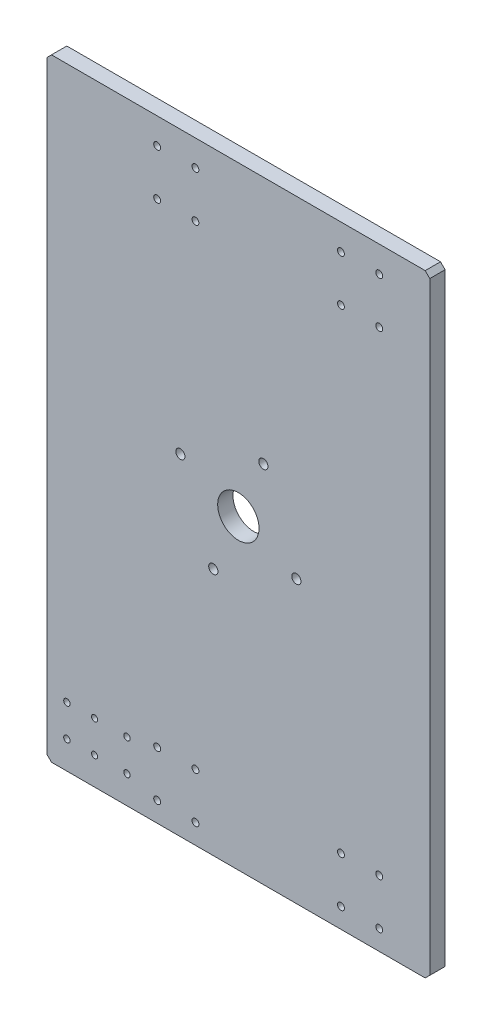
SolidWorks part; units mm, degrees
ref_plane "Plan de face" through (0, 0, 0) normal (0, 0, 1) x (1, 0, 0)
ref_plane "Plan de dessus" through (0, 0, 0) normal (0, 1, 0) x (1, 0, 0)
ref_plane "Plan de droite" through (0, 0, 0) normal (1, 0, 0) x (0, 0, -1)
sketch "Esquisse1" plane through (0, 0, 0) normal (0, 0, 1) x (1, 0, 0)
  line L1 (-125, -200) -> (125, -200)
  line L2 (-125, -200) -> (-125, 200)
  line L3 (-125, 200) -> (125, 200)
  line L4 (125, -200) -> (125, 200)
  line L5 (-125, -200) -> (125, 200) construction
  line L6 (-125, 200) -> (125, -200) construction
  point P0 (0, 0)
  dimension "D1" = 400
  dimension "D2" = 250
extrude "Boss.-Extru.1" add sketch "Esquisse1" along normal blind 10
ref_plane "Plan1" through (0, 0, 0) normal (1, 0, 0) x (0, 0, -1)
ref_plane "Plan2" through (0, 0, 0) normal (0, 1, 0) x (1, 0, 0)
sketch "Esquisse2" plane through (0, 0, 0) normal (0, 0, -1) x (-1, 0, 0)
  circle A0 centre (0, 0) radius 13.5
  dimension "D1" = 27
extrude "Enlèv. mat.-Extru.1" cut sketch "Esquisse2" against normal through all
chamfer "Chanfrein1" distance 3 angle 45 4 edges at (-125, -200, 5) (125, -200, 5) (125, 200, 5) (-125, 200, 5)
hole_wizard "Trou taraudé M51" positions "Esquisse6" profile "Esquisse5" tap size "M5" standard "ISO" end condition through all
sketch "Esquisse6" plane through (0, 0, 10) normal (0, 0, 1) x (1, 0, 0)
  point P0 (-72.6985, -161.0797)
  point P3 (-72.6985, -181.8387)
  point P6 (-111.9372, -181.8387)
  point P9 (-111.9372, -161.0797)
sketch "Esquisse5" plane through (-72.6985, -161.0797, 10) normal (1, 0, 0) x (0, -1, 0)
  line L0 (0, 0) -> (0, 10)
  line L1 (0, 10) -> (2.1, 10)
  line L2 (2.1, 10) -> (2.1, 0)
  line L5 (2.1, 0) -> (0, 0)
  line L11 (0, -6.35) -> (0, 107.95) construction
  dimension "Diamètre du trou pour taraudage jusqu'au prochain" = 4.2
  dimension "Profondeur du trou pour taraudage jusqu'au prochain" = 10
cosmetic thread "Filetage de perçage3" parameters "D2"=5
cosmetic thread "Filetage de perçage4" parameters "D2"=5
cosmetic thread "Filetage de perçage5" parameters "D2"=5
cosmetic thread "Filetage de perçage6" parameters "D2"=5
hole_wizard "Trous de centrage Ø4.0mm2" positions "Esquisse9" profile "Esquisse8" hole size "Ø4.0" standard "ISO" end condition through all
sketch "Esquisse9" plane through (0, 0, 10) normal (0, 0, 1) x (1, 0, 0)
  point P0 (-93.8631, -161.0797)
  point P3 (-93.8631, -181.8387)
sketch "Esquisse8" plane through (-93.8631, -161.0797, 10) normal (1, 0, 0) x (0, -1, 0)
  line L0 (0, 0) -> (0, 10)
  line L1 (0, 10) -> (2, 10)
  line L2 (2, 10) -> (2, 0)
  line L5 (2, 0) -> (0, 0)
  line L11 (0, -6.35) -> (0, 107.95) construction
  dimension "Diamètre du perçage jusqu'au prochain" = 4
  dimension "Profondeur du perçage jusqu'au prochain" = 10
sketch "Esquisse10" plane through (0, 0, 10) normal (0, 0, 1) x (1, 0, 0)
  circle A0 centre (0, 0) radius 41.25 construction
  dimension "D1" = 82.5
hole_wizard "Trous de centrage Ø6.0mm2" positions "Esquisse26" profile "Esquisse25" hole size "Ø6.0" standard "ISO" end condition through all
sketch "Esquisse26" plane through (0, 0, 10) normal (0, 0, 1) x (1, 0, 0)
  point P0 (16.3571, 37.8683)
  point P2 (37.8683, -16.3571)
  point P4 (-16.3571, -37.8683)
  point P6 (-37.8683, 16.3571)
sketch "Esquisse25" plane through (16.3571, 37.8683, 10) normal (1, 0, 0) x (0, -1, 0)
  line L0 (0, 0) -> (0, 10)
  line L1 (0, 10) -> (3, 10)
  line L2 (3, 10) -> (3, 0)
  line L5 (3, 0) -> (0, 0)
  line L11 (0, -6.35) -> (0, 107.95) construction
  dimension "Diamètre du perçage jusqu'au prochain" = 6
  dimension "Profondeur du perçage jusqu'au prochain" = 10
hole_wizard "Dégagement M41" positions "Esquisse28" profile "Esquisse27" hole size "M4" standard "JIS" end condition through all
sketch "Esquisse28" plane through (0, 0, 0) normal (0, 0, -1) x (-1, 0, 0)
  point P0 (28, -187)
  point P2 (28, -157)
  point P4 (53, -157)
  point P6 (53, -187)
sketch "Esquisse27" plane through (-28, -187, 0) normal (1, 0, 0) x (0, 1, 0)
  line L0 (0, 0) -> (0, 10)
  line L1 (0, 10) -> (2.25, 10)
  line L2 (2.25, 10) -> (2.25, 0)
  line L5 (2.25, 0) -> (0, 0)
  line L11 (0, -6.35) -> (0, 107.95) construction
  dimension "Diamètre du perçage jusqu'au prochain" = 4.5
  dimension "Profondeur du perçage jusqu'au prochain" = 10
pattern_linear "Répétition linéaire1" count 2 spacing 120 along (1, 0, 0) count 2 spacing 340 along (0, 1, 0) of "Dégagement M41"
